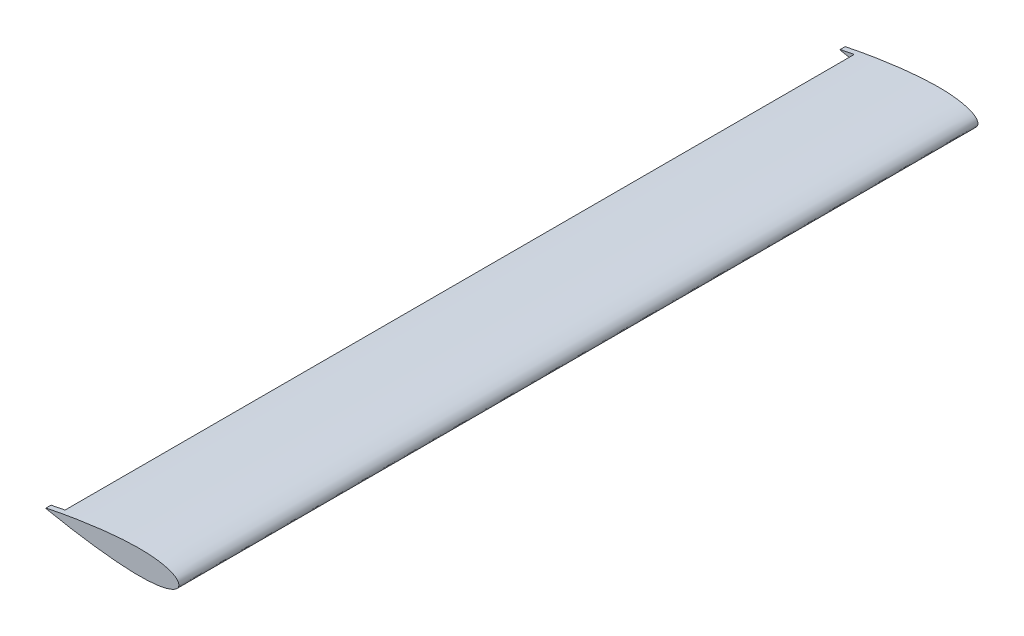
SolidWorks part; units mm, degrees
ref_plane "Alzado" through (0, 0, 0) normal (0, 0, 1) x (1, 0, 0)
ref_plane "Planta" through (0, 0, 0) normal (0, 1, 0) x (1, 0, 0)
ref_plane "Vista lateral" through (0, 0, 0) normal (1, 0, 0) x (0, 0, -1)
sketch "Croquis1" plane through (0, 0, 0) normal (0, 0, 1) x (1, 0, 0)
  line L0 (0, 0) -> (0, -23.5) construction
  line L1 (0, 0) -> (-16, 0) construction
  line L2 (-14.2698, -25.6618) -> (-26, -25.6618)
  line L3 (-26, -25.6618) -> (-26, -33.5)
  line L4 (-26, -33.5) -> (16, -33.5)
  line L5 (16, -33.5) -> (16, 3.8445)
  line L6 (16, 3.8445) -> (-14.2698, 3.8445)
  line L8 (-14.2698, -6.2762) -> (-14.2698, -25.6618)
  line L9 (-14.2698, 3.8445) -> (-26, 3.8445)
  line L10 (-26, 3.8445) -> (-26, -6.2762)
  line L11 (-26, -6.2762) -> (-14.2698, -6.2762)
  circle A0 centre (0, 0) radius 1.5
  dimension "D1" = 3
  dimension "D4" = 16
  dimension "D2" = 23.5
  dimension "D3" = 16
  dimension "D5" = 10
  dimension "D6" = 42
curve "Curva2"
  spline degree 3 poles (266, 0.503, 0) (261.5688, 1.4191, 0) (252.7164, 3.2493, 0) (234.9955, 6.6448, 0) (212.8433, 10.5485, 0) (186.2398, 14.7043, 0) (159.6407, 18.3128, 0) (133.0409, 21.2624, 0) (106.4348, 23.353, 0) (84.237, 24.0962, 0) (66.4893, 23.7999, 0) (53.1677, 23.0109, 0) (39.8211, 21.4881, 0) (28.7128, 19.3599, 0) (19.853, 16.8285, 0) (13.0874, 14.2708, 0) (7.4196, 11.1923, 0) (2.2073, 6.9321, 0) (-1.4404, 0, 0) (2.2073, -6.9321, 0) (7.4196, -11.1923, 0) (13.0874, -14.2708, 0) (19.853, -16.8285, 0) (28.7128, -19.3599, 0) (39.8211, -21.4881, 0) (53.1677, -23.0109, 0) (66.4893, -23.7999, 0) (84.237, -24.0962, 0) (106.4348, -23.353, 0) (133.0409, -21.2624, 0) (159.6407, -18.3128, 0) (186.2398, -14.7043, 0) (212.8433, -10.5485, 0) (234.9955, -6.6448, 0) (252.7164, -3.2493, 0) (261.5688, -1.4191, 0) (266, -0.503, 0) knots 0 0 0 0 0.024604 0.049152 0.098109 0.146905 0.195555 0.244056 0.292409 0.340644 0.364754 0.388905 0.413178 0.437756 0.450305 0.46323 0.477067 0.485036 0.5 0.514964 0.522933 0.53677 0.549695 0.562244 0.586822 0.611095 0.635246 0.659356 0.707591 0.755944 0.804445 0.853095 0.901891 0.950848 0.975396 1 1 1 1
sketch "Croquis6" plane through (0, 0, 0) normal (0, 0, 1) x (1, 0, 0)
  line L2 (-268.433, 0) -> (0, 0) construction
  line L4 (-266, 0.503) -> (-268.433, 0)
  line L5 (-266, -0.503) -> (-268.433, 0)
  spline S2 degree 3 poles (-266, 0.503) (-261.5688, 1.4191) (-252.7164, 3.2493) (-234.9955, 6.6448) (-212.8433, 10.5485) (-186.2398, 14.7043) (-159.6407, 18.3128) (-133.0409, 21.2624) (-106.4348, 23.353) (-84.237, 24.0962) (-66.4893, 23.7999) (-53.1677, 23.0109) (-39.8211, 21.4881) (-28.7128, 19.3599) (-19.853, 16.8285) (-13.0874, 14.2708) (-7.4196, 11.1923) (-2.2073, 6.9321) (1.4404, 0) (-2.2073, -6.9321) (-7.4196, -11.1923) (-13.0874, -14.2708) (-19.853, -16.8285) (-28.7128, -19.3599) (-39.8211, -21.4881) (-53.1677, -23.0109) (-66.4893, -23.7999) (-84.237, -24.0962) (-106.4348, -23.353) (-133.0409, -21.2624) (-159.6407, -18.3128) (-186.2398, -14.7043) (-212.8433, -10.5485) (-234.9955, -6.6448) (-252.7164, -3.2493) (-261.5688, -1.4191) (-266, -0.503) knots 0 0 0 0 0.024604 0.049152 0.098109 0.146905 0.195555 0.244056 0.292409 0.340644 0.364754 0.388905 0.413178 0.437756 0.450305 0.46323 0.477067 0.485036 0.5 0.514964 0.522933 0.53677 0.549695 0.562244 0.586822 0.611095 0.635246 0.659356 0.707591 0.755944 0.804445 0.853095 0.901891 0.950848 0.975396 1 1 1 1
  point P8 (0, 0)
  dimension "D1" = 268.433
sketch "Croquis7" plane through (0, 0, 0) normal (0, 0, 1) x (1, 0, 0)
  line L0 (-266, 0.503) -> (-268.433, 0) construction
  line L1 (-266, 0.503) -> (-268.433, 0) construction
  line L2 (-266, -0.503) -> (-268.433, 0) construction
  line L3 (-266, -0.503) -> (-268.433, 0) construction
  line L4 (-266, -0.503) -> (-266, 0.503)
  spline S0 degree 3 poles (-1155.1432, 1765.3014) (-594.7387, -117.8294) (-424.6464, -29.6947) (-234.9955, 6.6448) (-212.8433, 10.5485) (-186.2398, 14.7043) (-159.6407, 18.3128) (-133.0409, 21.2624) (-106.4348, 23.353) (-84.237, 24.0962) (-66.4893, 23.7999) (-53.1677, 23.0109) (-39.8211, 21.4881) (-28.7128, 19.3599) (-19.853, 16.8285) (-13.0874, 14.2708) (-7.4196, 11.1923) (-2.2073, 6.9321) (1.4404, 0) (-2.2073, -6.9321) (-7.4196, -11.1923) (-13.0874, -14.2708) (-19.853, -16.8285) (-28.7128, -19.3599) (-39.8211, -21.4881) (-53.1677, -23.0109) (-66.4893, -23.7999) (-84.237, -24.0962) (-106.4348, -23.353) (-133.0409, -21.2624) (-159.6407, -18.3128) (-186.2398, -14.7043) (-212.8433, -10.5485) (-234.9955, -6.6448) (-424.6458, 29.6946) (-594.7376, 117.8288) (-1155.1376, -1765.2827) knots -0.951855 -0.951855 -0.951855 -0.951855 0.024604 0.049152 0.098109 0.146905 0.195555 0.244056 0.292409 0.340644 0.364754 0.388905 0.413178 0.437756 0.450305 0.46323 0.477067 0.485036 0.5 0.514964 0.522933 0.53677 0.549695 0.562244 0.586822 0.611095 0.635246 0.659356 0.707591 0.755944 0.804445 0.853095 0.901891 0.950848 0.975396 1.951852 1.951852 1.951852 1.951852 only from (-266, 0.503) to (-266, -0.503) construction
  spline S1 degree 3 poles (-266, 0.503) (-261.5688, 1.4191) (-252.7164, 3.2493) (-234.9955, 6.6448) (-212.8433, 10.5485) (-186.2398, 14.7043) (-159.6407, 18.3128) (-133.0409, 21.2624) (-106.4348, 23.353) (-84.237, 24.0962) (-66.4893, 23.7999) (-53.1677, 23.0109) (-39.8211, 21.4881) (-28.7128, 19.3599) (-19.853, 16.8285) (-13.0874, 14.2708) (-7.4196, 11.1923) (-2.2073, 6.9321) (1.4404, 0) (-2.2073, -6.9321) (-7.4196, -11.1923) (-13.0874, -14.2708) (-19.853, -16.8285) (-28.7128, -19.3599) (-39.8211, -21.4881) (-53.1677, -23.0109) (-66.4893, -23.7999) (-84.237, -24.0962) (-106.4348, -23.353) (-133.0409, -21.2624) (-159.6407, -18.3128) (-186.2398, -14.7043) (-212.8433, -10.5485) (-234.9955, -6.6448) (-252.7164, -3.2493) (-261.5688, -1.4191) (-266, -0.503) knots 0 0 0 0 0.024604 0.049152 0.098109 0.146905 0.195555 0.244056 0.292409 0.340644 0.364754 0.388905 0.413178 0.437756 0.450305 0.46323 0.477067 0.485036 0.5 0.514964 0.522933 0.53677 0.549695 0.562244 0.586822 0.611095 0.635246 0.659356 0.707591 0.755944 0.804445 0.853095 0.901891 0.950848 0.975396 1 1 1 1
  point P2 (0, 0)
extrude "Saliente-Extruir1" add sketch "Croquis7" along normal mid plane 1600
sketch "Croquis8" plane through (0, 0, 0) normal (0, 0, 1) x (1, 0, 0)
  line L0 (-267.9302, -0.83) -> (-267.9302, 0.83)
  line L1 (-237.8077, -6.0739) -> (-237.8077, 6.0739)
  line L2 (-267.9302, -0.83) -> (-267.9302, 0.83) construction
  spline S0 degree 3 poles (-266, 0.503) (-261.5688, 1.4191) (-252.7164, 3.2493) (-234.9955, 6.6448) (-212.8433, 10.5485) (-186.2398, 14.7043) (-159.6407, 18.3128) (-133.0409, 21.2624) (-106.4348, 23.353) (-84.237, 24.0962) (-66.4893, 23.7999) (-53.1677, 23.0109) (-39.8211, 21.4881) (-28.7128, 19.3599) (-19.853, 16.8285) (-13.0874, 14.2708) (-7.4196, 11.1923) (-2.2073, 6.9321) (1.4404, 0) (-2.2073, -6.9321) (-7.4196, -11.1923) (-13.0874, -14.2708) (-19.853, -16.8285) (-28.7128, -19.3599) (-39.8211, -21.4881) (-53.1677, -23.0109) (-66.4893, -23.7999) (-84.237, -24.0962) (-106.4348, -23.353) (-133.0409, -21.2624) (-159.6407, -18.3128) (-186.2398, -14.7043) (-212.8433, -10.5485) (-234.9955, -6.6448) (-252.7164, -3.2493) (-261.5688, -1.4191) (-266, -0.503) knots 0 0 0 0 0.024604 0.049152 0.098109 0.146905 0.195555 0.244056 0.292409 0.340644 0.364754 0.388905 0.413178 0.437756 0.450305 0.46323 0.477067 0.485036 0.5 0.514964 0.522933 0.53677 0.549695 0.562244 0.586822 0.611095 0.635246 0.659356 0.707591 0.755944 0.804445 0.853095 0.901891 0.950848 0.975396 1 1 1 1 construction
  spline S1 degree 3 poles (-267.9302, 0.83) (-257.8902, 2.5829) (-247.8502, 4.3359) (-237.8077, 6.0739) knots 0 0 0 0 0.011104 0.011104 0.011104 0.011104
  spline S2 degree 3 poles (-237.8077, -6.0739) (-247.8502, -4.3359) (-257.8902, -2.5829) (-267.9302, -0.83) knots 0.988896 0.988896 0.988896 0.988896 1 1 1 1
  point P0 (-267.8077, 0.1694)
  point P1 (-260, -1.7404)
  point P2 (-260, 1.7404)
  point P9 (0, 0)
  point P10 (-236, -6.4075)
  point P11 (-236, -6.4075)
  point P12 (-266, 0.503)
  dimension "D2" = 1.6599
extrude "Cortar-Extruir1" cut sketch "Croquis8" against normal mid plane 1580
